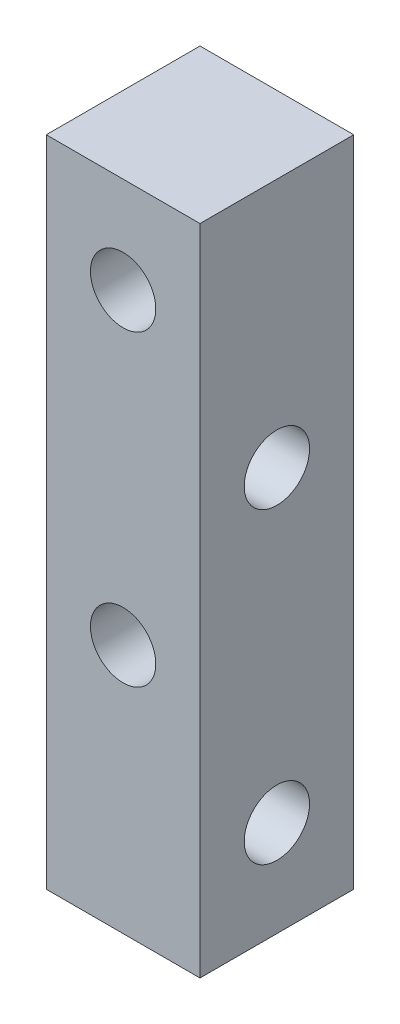
SolidWorks part; units mm, degrees
material "6061 合金"
ref_plane "前视基准面" through (0, 0, 0) normal (0, 0, 1) x (1, 0, 0)
ref_plane "上视基准面" through (0, 0, 0) normal (0, 1, 0) x (1, 0, 0)
ref_plane "右视基准面" through (0, 0, 0) normal (1, 0, 0) x (0, 0, -1)
other "Configuration Table"
sketch "草图1" plane through (0, 0, 0) normal (0, 1, 0) x (1, 0, 0)
  line L1 (4, -4) -> (-4, -4)
  line L2 (4, -4) -> (4, 4)
  line L3 (4, 4) -> (-4, 4)
  line L4 (-4, -4) -> (-4, 4)
  line L5 (4, -4) -> (-4, 4) construction
  line L6 (4, 4) -> (-4, -4) construction
  point P0 (0, 0)
  dimension "D1" = 8
  dimension "D2" = 8
extrude "凸台-拉伸1" add sketch "草图1" along normal blind 34
sketch "草图2" plane through (0, 0, -4) normal (0, 0, -1) x (-1, 0, 0)
  line L0 (0, 34) -> (0, 0) construction
  line L1 (-4, 34) -> (4, 34) construction
  circle A0 centre (0, 29) radius 1.7
  circle A1 centre (0, 13) radius 1.7
  dimension "D2" = 3.4
  dimension "D3" = 3.4
  dimension "D4" = 16
  dimension "D1" = 5
extrude "切除-拉伸1" cut sketch "草图2" against normal blind 34
sketch "草图3" plane through (4, 0, 0) normal (1, 0, 0) x (0, 0, -1)
  line L0 (0, 0) -> (0, 34) construction
  line L1 (-4, 34) -> (4, 34) construction
  line L2 (-4, 0) -> (4, 0) construction
  circle A0 centre (0, 5) radius 1.7
  circle A2 centre (0, 21) radius 1.7
  dimension "D1" = 3.4
  dimension "D2" = 5
  dimension "D3" = 16
  dimension "D4" = 3.4
extrude "切除-拉伸2" cut sketch "草图3" against normal blind 34
